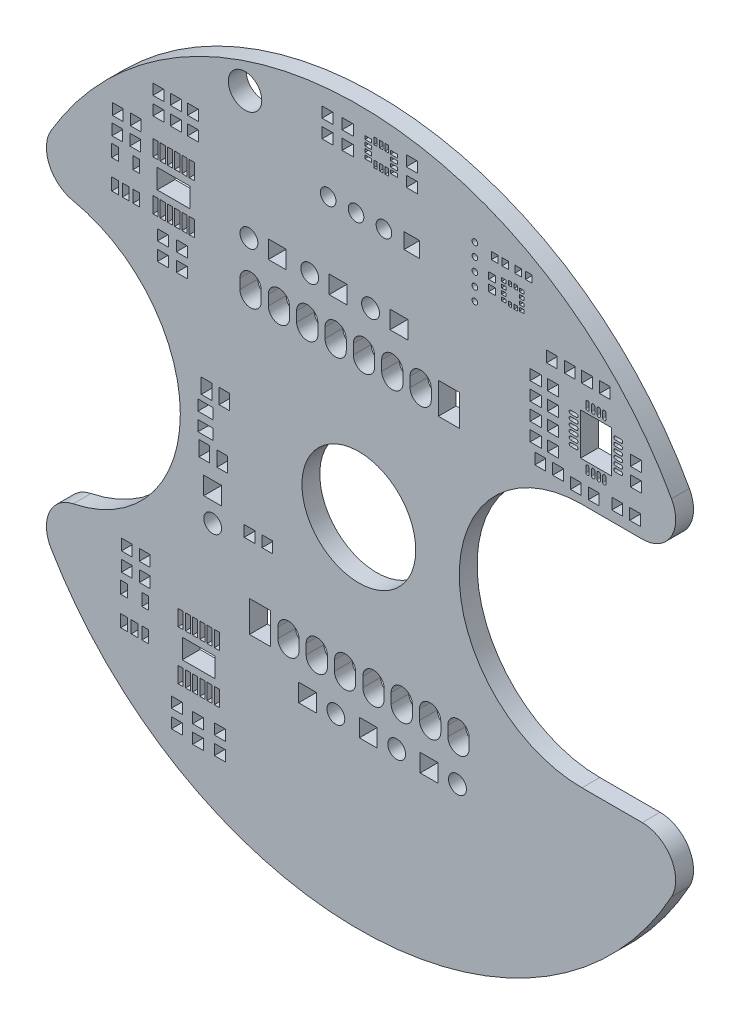
SolidWorks part; units mm, degrees
ref_plane "Plan de face" through (0, 0, 0) normal (0, 0, 1) x (1, 0, 0)
ref_plane "Plan de dessus" through (0, 0, 0) normal (0, 1, 0) x (1, 0, 0)
ref_plane "Plan de droite" through (0, 0, 0) normal (1, 0, 0) x (0, 0, -1)
sketch "Model" plane through (0, 0, 0) normal (0, 0, 1) x (1, 0, 0)
  line L0 (14.8, 23.5) -> (14.8, 23.2)
  line L1 (14.8, 23.2) -> (14.4, 23.2)
  line L2 (14.4, 23.2) -> (14.4, 23.5)
  line L3 (14.4, 23.5) -> (14.8, 23.5)
  line L4 (14.8, 24) -> (14.8, 23.7)
  line L5 (14.8, 23.7) -> (14.4, 23.7)
  line L6 (14.4, 23.7) -> (14.4, 24)
  line L7 (14.4, 24) -> (14.8, 24)
  line L8 (14.8, 24.5) -> (14.8, 24.2)
  line L9 (14.8, 24.2) -> (14.4, 24.2)
  line L10 (14.4, 24.2) -> (14.4, 24.5)
  line L11 (14.4, 24.5) -> (14.8, 24.5)
  line L12 (14.8, 25) -> (14.8, 24.7)
  line L13 (14.8, 24.7) -> (14.4, 24.7)
  line L14 (14.4, 24.7) -> (14.4, 25)
  line L15 (14.4, 25) -> (14.8, 25)
  line L16 (13.9, 25.1) -> (14.2, 25.1)
  line L17 (14.2, 25.1) -> (14.2, 24.7)
  line L18 (14.2, 24.7) -> (13.9, 24.7)
  line L19 (13.9, 24.7) -> (13.9, 25.1)
  line L20 (13.4, 25.1) -> (13.7, 25.1)
  line L21 (13.7, 25.1) -> (13.7, 24.7)
  line L22 (13.7, 24.7) -> (13.4, 24.7)
  line L23 (13.4, 24.7) -> (13.4, 25.1)
  line L24 (13.2, 25) -> (13.2, 24.7)
  line L25 (13.2, 24.7) -> (12.8, 24.7)
  line L26 (12.8, 24.7) -> (12.8, 25)
  line L27 (12.8, 25) -> (13.2, 25)
  line L28 (13.2, 24.5) -> (13.2, 24.2)
  line L29 (13.2, 24.2) -> (12.8, 24.2)
  line L30 (12.8, 24.2) -> (12.8, 24.5)
  line L31 (12.8, 24.5) -> (13.2, 24.5)
  line L32 (13.2, 24) -> (13.2, 23.7)
  line L33 (13.2, 23.7) -> (12.8, 23.7)
  line L34 (12.8, 23.7) -> (12.8, 24)
  line L35 (12.8, 24) -> (13.2, 24)
  line L36 (13.2, 23.5) -> (13.2, 23.2)
  line L37 (13.2, 23.2) -> (12.8, 23.2)
  line L38 (12.8, 23.2) -> (12.8, 23.5)
  line L39 (12.8, 23.5) -> (13.2, 23.5)
  line L40 (13.4, 23.5) -> (13.7, 23.5)
  line L41 (13.7, 23.5) -> (13.7, 23.1)
  line L42 (13.7, 23.1) -> (13.4, 23.1)
  line L43 (13.4, 23.1) -> (13.4, 23.5)
  line L44 (13.9, 23.5) -> (14.2, 23.5)
  line L45 (14.2, 23.5) -> (14.2, 23.1)
  line L46 (14.2, 23.1) -> (13.9, 23.1)
  line L47 (13.9, 23.1) -> (13.9, 23.5)
  line L48 (14.565, 25.93) -> (13.975, 25.93)
  line L49 (13.975, 25.93) -> (13.975, 26.57)
  line L50 (13.975, 26.57) -> (14.565, 26.57)
  line L51 (14.565, 26.57) -> (14.565, 25.93)
  line L52 (15.525, 25.93) -> (14.935, 25.93)
  line L53 (14.935, 25.93) -> (14.935, 26.57)
  line L54 (14.935, 26.57) -> (15.525, 26.57)
  line L55 (15.525, 26.57) -> (15.525, 25.93)
  line L56 (12.835, 26.57) -> (13.425, 26.57)
  line L57 (13.425, 26.57) -> (13.425, 25.93)
  line L58 (13.425, 25.93) -> (12.835, 25.93)
  line L59 (12.835, 25.93) -> (12.835, 26.57)
  line L60 (11.875, 26.57) -> (12.465, 26.57)
  line L61 (12.465, 26.57) -> (12.465, 25.93)
  line L62 (12.465, 25.93) -> (11.875, 25.93)
  line L63 (11.875, 25.93) -> (11.875, 26.57)
  line L64 (11.63, 24.285) -> (11.63, 24.875)
  line L65 (11.63, 24.875) -> (12.27, 24.875)
  line L66 (12.27, 24.875) -> (12.27, 24.285)
  line L67 (12.27, 24.285) -> (11.63, 24.285)
  line L68 (11.63, 23.325) -> (11.63, 23.915)
  line L69 (11.63, 23.915) -> (12.27, 23.915)
  line L70 (12.27, 23.915) -> (12.27, 23.325)
  line L71 (12.27, 23.325) -> (11.63, 23.325)
  line L72 (-12.725, -1.125) -> (-11.775, -1.125)
  line L73 (-11.775, -1.125) -> (-11.775, -2.475)
  line L74 (-11.775, -2.475) -> (-12.725, -2.475)
  line L75 (-12.725, -2.475) -> (-12.725, -1.125)
  line L76 (-14.325, -1.125) -> (-13.375, -1.125)
  line L77 (-13.375, -1.125) -> (-13.375, -2.475)
  line L78 (-13.375, -2.475) -> (-14.325, -2.475)
  line L79 (-14.325, -2.475) -> (-14.325, -1.125)
  line L80 (-12.525, 3.825) -> (-11.575, 3.825)
  line L81 (-11.575, 3.825) -> (-11.575, 2.475)
  line L82 (-11.575, 2.475) -> (-12.525, 2.475)
  line L83 (-12.525, 2.475) -> (-12.525, 3.825)
  line L84 (-14.125, 3.825) -> (-13.175, 3.825)
  line L85 (-13.175, 3.825) -> (-13.175, 2.475)
  line L86 (-13.175, 2.475) -> (-14.125, 2.475)
  line L87 (-14.125, 2.475) -> (-14.125, 3.825)
  line L88 (-13.075, 0.375) -> (-13.075, -0.575)
  line L89 (-13.075, -0.575) -> (-14.425, -0.575)
  line L90 (-14.425, -0.575) -> (-14.425, 0.375)
  line L91 (-14.425, 0.375) -> (-13.075, 0.375)
  line L92 (-13.075, 1.975) -> (-13.075, 1.025)
  line L93 (-13.075, 1.025) -> (-14.425, 1.025)
  line L94 (-14.425, 1.025) -> (-14.425, 1.975)
  line L95 (-14.425, 1.975) -> (-13.075, 1.975)
  line L96 (-21.55, 14.25) -> (-22.15, 14.25)
  line L97 (-22.15, 14.25) -> (-22.15, 15.35)
  line L98 (-22.15, 15.35) -> (-21.55, 15.35)
  line L99 (-21.55, 15.35) -> (-21.55, 14.25)
  line L100 (-20.6, 14.25) -> (-21.2, 14.25)
  line L101 (-21.2, 14.25) -> (-21.2, 15.35)
  line L102 (-21.2, 15.35) -> (-20.6, 15.35)
  line L103 (-20.6, 15.35) -> (-20.6, 14.25)
  line L104 (-19.65, 14.25) -> (-20.25, 14.25)
  line L105 (-20.25, 14.25) -> (-20.25, 15.35)
  line L106 (-20.25, 15.35) -> (-19.65, 15.35)
  line L107 (-19.65, 15.35) -> (-19.65, 14.25)
  line L108 (-19.65, 16.85) -> (-20.25, 16.85)
  line L109 (-20.25, 16.85) -> (-20.25, 17.95)
  line L110 (-20.25, 17.95) -> (-19.65, 17.95)
  line L111 (-19.65, 17.95) -> (-19.65, 16.85)
  line L112 (-21.55, 16.85) -> (-22.15, 16.85)
  line L113 (-22.15, 16.85) -> (-22.15, 17.95)
  line L114 (-22.15, 17.95) -> (-21.55, 17.95)
  line L115 (-21.55, 17.95) -> (-21.55, 16.85)
  line L116 (-20.75, -19.25) -> (-21.35, -19.25)
  line L117 (-21.35, -19.25) -> (-21.35, -18.15)
  line L118 (-21.35, -18.15) -> (-20.75, -18.15)
  line L119 (-20.75, -18.15) -> (-20.75, -19.25)
  line L120 (-19.8, -19.25) -> (-20.4, -19.25)
  line L121 (-20.4, -19.25) -> (-20.4, -18.15)
  line L122 (-20.4, -18.15) -> (-19.8, -18.15)
  line L123 (-19.8, -18.15) -> (-19.8, -19.25)
  line L124 (-18.85, -19.25) -> (-19.45, -19.25)
  line L125 (-19.45, -19.25) -> (-19.45, -18.15)
  line L126 (-19.45, -18.15) -> (-18.85, -18.15)
  line L127 (-18.85, -18.15) -> (-18.85, -19.25)
  line L128 (-18.85, -16.65) -> (-19.45, -16.65)
  line L129 (-19.45, -16.65) -> (-19.45, -15.55)
  line L130 (-19.45, -15.55) -> (-18.85, -15.55)
  line L131 (-18.85, -15.55) -> (-18.85, -16.65)
  line L132 (-20.75, -16.65) -> (-21.35, -16.65)
  line L133 (-21.35, -16.65) -> (-21.35, -15.55)
  line L134 (-21.35, -15.55) -> (-20.75, -15.55)
  line L135 (-20.75, -15.55) -> (-20.75, -16.65)
  line L136 (-18, 15.7505) -> (-18, 14.3255)
  line L137 (-18, 14.3255) -> (-18.45, 14.3255)
  line L138 (-18.45, 14.3255) -> (-18.45, 15.7505)
  line L139 (-18.45, 15.7505) -> (-18, 15.7505)
  line L140 (-17.35, 15.7505) -> (-17.35, 14.3255)
  line L141 (-17.35, 14.3255) -> (-17.8, 14.3255)
  line L142 (-17.8, 14.3255) -> (-17.8, 15.7505)
  line L143 (-17.8, 15.7505) -> (-17.35, 15.7505)
  line L144 (-16.7, 15.7505) -> (-16.7, 14.3255)
  line L145 (-16.7, 14.3255) -> (-17.15, 14.3255)
  line L146 (-17.15, 14.3255) -> (-17.15, 15.7505)
  line L147 (-17.15, 15.7505) -> (-16.7, 15.7505)
  line L148 (-16.05, 15.7505) -> (-16.05, 14.3255)
  line L149 (-16.05, 14.3255) -> (-16.5, 14.3255)
  line L150 (-16.5, 14.3255) -> (-16.5, 15.7505)
  line L151 (-16.5, 15.7505) -> (-16.05, 15.7505)
  line L152 (-15.4, 15.7505) -> (-15.4, 14.3255)
  line L153 (-15.4, 14.3255) -> (-15.85, 14.3255)
  line L154 (-15.85, 14.3255) -> (-15.85, 15.7505)
  line L155 (-15.85, 15.7505) -> (-15.4, 15.7505)
  line L156 (-14.75, 15.7505) -> (-14.75, 14.3255)
  line L157 (-14.75, 14.3255) -> (-15.2, 14.3255)
  line L158 (-15.2, 14.3255) -> (-15.2, 15.7505)
  line L159 (-15.2, 15.7505) -> (-14.75, 15.7505)
  line L160 (-14.75, 20.1745) -> (-14.75, 18.7495)
  line L161 (-14.75, 18.7495) -> (-15.2, 18.7495)
  line L162 (-15.2, 18.7495) -> (-15.2, 20.1745)
  line L163 (-15.2, 20.1745) -> (-14.75, 20.1745)
  line L164 (-15.4, 20.1745) -> (-15.4, 18.7495)
  line L165 (-15.4, 18.7495) -> (-15.85, 18.7495)
  line L166 (-15.85, 18.7495) -> (-15.85, 20.1745)
  line L167 (-15.85, 20.1745) -> (-15.4, 20.1745)
  line L168 (-16.05, 20.1745) -> (-16.05, 18.7495)
  line L169 (-16.05, 18.7495) -> (-16.5, 18.7495)
  line L170 (-16.5, 18.7495) -> (-16.5, 20.1745)
  line L171 (-16.5, 20.1745) -> (-16.05, 20.1745)
  line L172 (-16.7, 20.1745) -> (-16.7, 18.7495)
  line L173 (-16.7, 18.7495) -> (-17.15, 18.7495)
  line L174 (-17.15, 18.7495) -> (-17.15, 20.1745)
  line L175 (-17.15, 20.1745) -> (-16.7, 20.1745)
  line L176 (-17.35, 20.1745) -> (-17.35, 18.7495)
  line L177 (-17.35, 18.7495) -> (-17.8, 18.7495)
  line L178 (-17.8, 18.7495) -> (-17.8, 20.1745)
  line L179 (-17.8, 20.1745) -> (-17.35, 20.1745)
  line L180 (-18, 20.1745) -> (-18, 18.7495)
  line L181 (-18, 18.7495) -> (-18.45, 18.7495)
  line L182 (-18.45, 18.7495) -> (-18.45, 20.1745)
  line L183 (-18.45, 20.1745) -> (-18, 20.1745)
  line L184 (-18.0735, 18.1265) -> (-15.1265, 18.1265)
  line L185 (-15.1265, 18.1265) -> (-15.1265, 16.3735)
  line L186 (-15.1265, 16.3735) -> (-18.0735, 16.3735)
  line L187 (-18.0735, 16.3735) -> (-18.0735, 18.1265)
  line L188 (-12.95, -16.6005) -> (-12.95, -15.1755)
  line L189 (-12.95, -15.1755) -> (-12.5, -15.1755)
  line L190 (-12.5, -15.1755) -> (-12.5, -16.6005)
  line L191 (-12.5, -16.6005) -> (-12.95, -16.6005)
  line L192 (-13.6, -16.6005) -> (-13.6, -15.1755)
  line L193 (-13.6, -15.1755) -> (-13.15, -15.1755)
  line L194 (-13.15, -15.1755) -> (-13.15, -16.6005)
  line L195 (-13.15, -16.6005) -> (-13.6, -16.6005)
  line L196 (-14.25, -16.6005) -> (-14.25, -15.1755)
  line L197 (-14.25, -15.1755) -> (-13.8, -15.1755)
  line L198 (-13.8, -15.1755) -> (-13.8, -16.6005)
  line L199 (-13.8, -16.6005) -> (-14.25, -16.6005)
  line L200 (-14.9, -16.6005) -> (-14.9, -15.1755)
  line L201 (-14.9, -15.1755) -> (-14.45, -15.1755)
  line L202 (-14.45, -15.1755) -> (-14.45, -16.6005)
  line L203 (-14.45, -16.6005) -> (-14.9, -16.6005)
  line L204 (-15.55, -16.6005) -> (-15.55, -15.1755)
  line L205 (-15.55, -15.1755) -> (-15.1, -15.1755)
  line L206 (-15.1, -15.1755) -> (-15.1, -16.6005)
  line L207 (-15.1, -16.6005) -> (-15.55, -16.6005)
  line L208 (-16.2, -16.6005) -> (-16.2, -15.1755)
  line L209 (-16.2, -15.1755) -> (-15.75, -15.1755)
  line L210 (-15.75, -15.1755) -> (-15.75, -16.6005)
  line L211 (-15.75, -16.6005) -> (-16.2, -16.6005)
  line L212 (-16.2, -21.0245) -> (-16.2, -19.5995)
  line L213 (-16.2, -19.5995) -> (-15.75, -19.5995)
  line L214 (-15.75, -19.5995) -> (-15.75, -21.0245)
  line L215 (-15.75, -21.0245) -> (-16.2, -21.0245)
  line L216 (-15.55, -21.0245) -> (-15.55, -19.5995)
  line L217 (-15.55, -19.5995) -> (-15.1, -19.5995)
  line L218 (-15.1, -19.5995) -> (-15.1, -21.0245)
  line L219 (-15.1, -21.0245) -> (-15.55, -21.0245)
  line L220 (-14.9, -21.0245) -> (-14.9, -19.5995)
  line L221 (-14.9, -19.5995) -> (-14.45, -19.5995)
  line L222 (-14.45, -19.5995) -> (-14.45, -21.0245)
  line L223 (-14.45, -21.0245) -> (-14.9, -21.0245)
  line L224 (-14.25, -21.0245) -> (-14.25, -19.5995)
  line L225 (-14.25, -19.5995) -> (-13.8, -19.5995)
  line L226 (-13.8, -19.5995) -> (-13.8, -21.0245)
  line L227 (-13.8, -21.0245) -> (-14.25, -21.0245)
  line L228 (-13.6, -21.0245) -> (-13.6, -19.5995)
  line L229 (-13.6, -19.5995) -> (-13.15, -19.5995)
  line L230 (-13.15, -19.5995) -> (-13.15, -21.0245)
  line L231 (-13.15, -21.0245) -> (-13.6, -21.0245)
  line L232 (-12.95, -21.0245) -> (-12.95, -19.5995)
  line L233 (-12.95, -19.5995) -> (-12.5, -19.5995)
  line L234 (-12.5, -19.5995) -> (-12.5, -21.0245)
  line L235 (-12.5, -21.0245) -> (-12.95, -21.0245)
  line L236 (-12.8765, -18.9765) -> (-15.8235, -18.9765)
  line L237 (-15.8235, -18.9765) -> (-15.8235, -17.2235)
  line L238 (-15.8235, -17.2235) -> (-12.8765, -17.2235)
  line L239 (-12.8765, -17.2235) -> (-12.8765, -18.9765)
  line L240 (9.0325, 14.197) -> (9.0325, 11.403)
  line L241 (9.0325, 11.403) -> (7.1275, 11.403)
  line L242 (7.1275, 11.403) -> (7.1275, 14.197)
  line L243 (7.1275, 14.197) -> (9.0325, 14.197)
  line L244 (4.5875, 12.3555) -> (4.5875, 13.2445)
  line L245 (6.4925, 13.2445) -> (6.4925, 12.3555)
  line L246 (2.0475, 12.3555) -> (2.0475, 13.2445)
  line L247 (3.9525, 13.2445) -> (3.9525, 12.3555)
  line L248 (-0.4925, 12.3555) -> (-0.4925, 13.2445)
  line L249 (1.4125, 13.2445) -> (1.4125, 12.3555)
  line L250 (-3.0325, 12.3555) -> (-3.0325, 13.2445)
  line L251 (-1.1275, 13.2445) -> (-1.1275, 12.3555)
  line L252 (-5.5725, 12.3555) -> (-5.5725, 13.2445)
  line L253 (-3.6675, 13.2445) -> (-3.6675, 12.3555)
  line L254 (-8.1125, 12.3555) -> (-8.1125, 13.2445)
  line L255 (-6.2075, 13.2445) -> (-6.2075, 12.3555)
  line L256 (-10.6525, 12.3555) -> (-10.6525, 13.2445)
  line L257 (-8.7475, 13.2445) -> (-8.7475, 12.3555)
  line L258 (-9.8025, -13.997) -> (-9.8025, -11.203)
  line L259 (-9.8025, -11.203) -> (-7.8975, -11.203)
  line L260 (-7.8975, -11.203) -> (-7.8975, -13.997)
  line L261 (-7.8975, -13.997) -> (-9.8025, -13.997)
  line L262 (-5.3575, -12.1555) -> (-5.3575, -13.0445)
  line L263 (-7.2625, -13.0445) -> (-7.2625, -12.1555)
  line L264 (-2.8175, -12.1555) -> (-2.8175, -13.0445)
  line L265 (-4.7225, -13.0445) -> (-4.7225, -12.1555)
  line L266 (-0.2775, -12.1555) -> (-0.2775, -13.0445)
  line L267 (-2.1825, -13.0445) -> (-2.1825, -12.1555)
  line L268 (2.2625, -12.1555) -> (2.2625, -13.0445)
  line L269 (0.3575, -13.0445) -> (0.3575, -12.1555)
  line L270 (4.8025, -12.1555) -> (4.8025, -13.0445)
  line L271 (2.8975, -13.0445) -> (2.8975, -12.1555)
  line L272 (7.3425, -12.1555) -> (7.3425, -13.0445)
  line L273 (5.4375, -13.0445) -> (5.4375, -12.1555)
  line L274 (9.8825, -12.1555) -> (9.8825, -13.0445)
  line L275 (7.9775, -13.0445) -> (7.9775, -12.1555)
  line L276 (3.45, 28.4) -> (3.45, 28.1)
  line L277 (3.45, 28.1) -> (2.85, 28.1)
  line L278 (2.85, 28.1) -> (2.85, 28.4)
  line L279 (2.85, 28.4) -> (3.45, 28.4)
  line L280 (3.45, 28.9) -> (3.45, 28.6)
  line L281 (3.45, 28.6) -> (2.85, 28.6)
  line L282 (2.85, 28.6) -> (2.85, 28.9)
  line L283 (2.85, 28.9) -> (3.45, 28.9)
  line L284 (3.45, 29.4) -> (3.45, 29.1)
  line L285 (3.45, 29.1) -> (2.85, 29.1)
  line L286 (2.85, 29.1) -> (2.85, 29.4)
  line L287 (2.85, 29.4) -> (3.45, 29.4)
  line L288 (3.45, 29.9) -> (3.45, 29.6)
  line L289 (3.45, 29.6) -> (2.85, 29.6)
  line L290 (2.85, 29.6) -> (2.85, 29.9)
  line L291 (2.85, 29.9) -> (3.45, 29.9)
  line L292 (2.35, 30.2) -> (2.65, 30.2)
  line L293 (2.65, 30.2) -> (2.65, 29.6)
  line L294 (2.65, 29.6) -> (2.35, 29.6)
  line L295 (2.35, 29.6) -> (2.35, 30.2)
  line L296 (1.85, 30.2) -> (2.15, 30.2)
  line L297 (2.15, 30.2) -> (2.15, 29.6)
  line L298 (2.15, 29.6) -> (1.85, 29.6)
  line L299 (1.85, 29.6) -> (1.85, 30.2)
  line L300 (1.35, 30.2) -> (1.65, 30.2)
  line L301 (1.65, 30.2) -> (1.65, 29.6)
  line L302 (1.65, 29.6) -> (1.35, 29.6)
  line L303 (1.35, 29.6) -> (1.35, 30.2)
  line L304 (1.15, 29.9) -> (1.15, 29.6)
  line L305 (1.15, 29.6) -> (0.55, 29.6)
  line L306 (0.55, 29.6) -> (0.55, 29.9)
  line L307 (0.55, 29.9) -> (1.15, 29.9)
  line L308 (1.15, 29.4) -> (1.15, 29.1)
  line L309 (1.15, 29.1) -> (0.55, 29.1)
  line L310 (0.55, 29.1) -> (0.55, 29.4)
  line L311 (0.55, 29.4) -> (1.15, 29.4)
  line L312 (1.15, 28.9) -> (1.15, 28.6)
  line L313 (1.15, 28.6) -> (0.55, 28.6)
  line L314 (0.55, 28.6) -> (0.55, 28.9)
  line L315 (0.55, 28.9) -> (1.15, 28.9)
  line L316 (1.15, 28.4) -> (1.15, 28.1)
  line L317 (1.15, 28.1) -> (0.55, 28.1)
  line L318 (0.55, 28.1) -> (0.55, 28.4)
  line L319 (0.55, 28.4) -> (1.15, 28.4)
  line L320 (1.35, 28.4) -> (1.65, 28.4)
  line L321 (1.65, 28.4) -> (1.65, 27.8)
  line L322 (1.65, 27.8) -> (1.35, 27.8)
  line L323 (1.35, 27.8) -> (1.35, 28.4)
  line L324 (1.85, 28.4) -> (2.15, 28.4)
  line L325 (2.15, 28.4) -> (2.15, 27.8)
  line L326 (2.15, 27.8) -> (1.85, 27.8)
  line L327 (1.85, 27.8) -> (1.85, 28.4)
  line L328 (2.35, 28.4) -> (2.65, 28.4)
  line L329 (2.65, 28.4) -> (2.65, 27.8)
  line L330 (2.65, 27.8) -> (2.35, 27.8)
  line L331 (2.35, 27.8) -> (2.35, 28.4)
  line L332 (23, 15.3) -> (23.5, 15.3)
  line L333 (23.5, 15) -> (23, 15)
  line L334 (23, 15.8) -> (23.5, 15.8)
  line L335 (23.5, 15.5) -> (23, 15.5)
  line L336 (23, 16.3) -> (23.5, 16.3)
  line L337 (23.5, 16) -> (23, 16)
  line L338 (23, 16.8) -> (23.5, 16.8)
  line L339 (23.5, 16.5) -> (23, 16.5)
  line L340 (23, 17.3) -> (23.5, 17.3)
  line L341 (23.5, 17) -> (23, 17)
  line L342 (23, 17.8) -> (23.5, 17.8)
  line L343 (23.5, 17.5) -> (23, 17.5)
  line L344 (21.85, 18.65) -> (21.85, 19.15)
  line L345 (22.15, 19.15) -> (22.15, 18.65)
  line L346 (21.35, 18.65) -> (21.35, 19.15)
  line L347 (21.65, 19.15) -> (21.65, 18.65)
  line L348 (20.85, 18.65) -> (20.85, 19.15)
  line L349 (21.15, 19.15) -> (21.15, 18.65)
  line L350 (20.35, 18.65) -> (20.35, 19.15)
  line L351 (20.65, 19.15) -> (20.65, 18.65)
  line L352 (19, 17.8) -> (19.5, 17.8)
  line L353 (19.5, 17.5) -> (19, 17.5)
  line L354 (19, 17.3) -> (19.5, 17.3)
  line L355 (19.5, 17) -> (19, 17)
  line L356 (19, 16.8) -> (19.5, 16.8)
  line L357 (19.5, 16.5) -> (19, 16.5)
  line L358 (19, 16.3) -> (19.5, 16.3)
  line L359 (19.5, 16) -> (19, 16)
  line L360 (19, 15.8) -> (19.5, 15.8)
  line L361 (19.5, 15.5) -> (19, 15.5)
  line L362 (19, 15.3) -> (19.5, 15.3)
  line L363 (19.5, 15) -> (19, 15)
  line L364 (20.35, 13.65) -> (20.35, 14.15)
  line L365 (20.65, 14.15) -> (20.65, 13.65)
  line L366 (20.85, 13.65) -> (20.85, 14.15)
  line L367 (21.15, 14.15) -> (21.15, 13.65)
  line L368 (21.35, 13.65) -> (21.35, 14.15)
  line L369 (21.65, 14.15) -> (21.65, 13.65)
  line L370 (21.85, 13.65) -> (21.85, 14.15)
  line L371 (22.15, 14.15) -> (22.15, 13.65)
  line L372 (22.625, 18.275) -> (22.625, 14.525)
  line L373 (22.625, 14.525) -> (19.875, 14.525)
  line L374 (19.875, 14.525) -> (19.875, 18.275)
  line L375 (19.875, 18.275) -> (22.625, 18.275)
  line L376 (-9.325, -6.7) -> (-10.275, -6.7)
  line L377 (-10.275, -6.7) -> (-10.275, -5.7)
  line L378 (-10.275, -5.7) -> (-9.325, -5.7)
  line L379 (-9.325, -5.7) -> (-9.325, -6.7)
  line L380 (-7.725, -6.7) -> (-8.675, -6.7)
  line L381 (-8.675, -6.7) -> (-8.675, -5.7)
  line L382 (-8.675, -5.7) -> (-7.725, -5.7)
  line L383 (-7.725, -5.7) -> (-7.725, -6.7)
  line L384 (-21.125, 20.15) -> (-22.075, 20.15)
  line L385 (-22.075, 20.15) -> (-22.075, 21.15)
  line L386 (-22.075, 21.15) -> (-21.125, 21.15)
  line L387 (-21.125, 21.15) -> (-21.125, 20.15)
  line L388 (-19.525, 20.15) -> (-20.475, 20.15)
  line L389 (-20.475, 20.15) -> (-20.475, 21.15)
  line L390 (-20.475, 21.15) -> (-19.525, 21.15)
  line L391 (-19.525, 21.15) -> (-19.525, 20.15)
  line L392 (-20.325, -13.25) -> (-21.275, -13.25)
  line L393 (-21.275, -13.25) -> (-21.275, -12.25)
  line L394 (-21.275, -12.25) -> (-20.325, -12.25)
  line L395 (-20.325, -12.25) -> (-20.325, -13.25)
  line L396 (-18.725, -13.25) -> (-19.675, -13.25)
  line L397 (-19.675, -13.25) -> (-19.675, -12.25)
  line L398 (-19.675, -12.25) -> (-18.725, -12.25)
  line L399 (-18.725, -12.25) -> (-18.725, -13.25)
  line L400 (-21.175, 18.55) -> (-22.125, 18.55)
  line L401 (-22.125, 18.55) -> (-22.125, 19.55)
  line L402 (-22.125, 19.55) -> (-21.175, 19.55)
  line L403 (-21.175, 19.55) -> (-21.175, 18.55)
  line L404 (-19.575, 18.55) -> (-20.525, 18.55)
  line L405 (-20.525, 18.55) -> (-20.525, 19.55)
  line L406 (-20.525, 19.55) -> (-19.575, 19.55)
  line L407 (-19.575, 19.55) -> (-19.575, 18.55)
  line L408 (-20.325, -14.9) -> (-21.275, -14.9)
  line L409 (-21.275, -14.9) -> (-21.275, -13.9)
  line L410 (-21.275, -13.9) -> (-20.325, -13.9)
  line L411 (-20.325, -13.9) -> (-20.325, -14.9)
  line L412 (-18.725, -14.9) -> (-19.675, -14.9)
  line L413 (-19.675, -14.9) -> (-19.675, -13.9)
  line L414 (-19.675, -13.9) -> (-18.725, -13.9)
  line L415 (-18.725, -13.9) -> (-18.725, -14.9)
  line L416 (-18.45, 23.525) -> (-18.45, 24.475)
  line L417 (-18.45, 24.475) -> (-17.45, 24.475)
  line L418 (-17.45, 24.475) -> (-17.45, 23.525)
  line L419 (-17.45, 23.525) -> (-18.45, 23.525)
  line L420 (-18.45, 21.925) -> (-18.45, 22.875)
  line L421 (-18.45, 22.875) -> (-17.45, 22.875)
  line L422 (-17.45, 22.875) -> (-17.45, 21.925)
  line L423 (-17.45, 21.925) -> (-18.45, 21.925)
  line L424 (20.925, 20.4) -> (19.975, 20.4)
  line L425 (19.975, 20.4) -> (19.975, 21.4)
  line L426 (19.975, 21.4) -> (20.925, 21.4)
  line L427 (20.925, 21.4) -> (20.925, 20.4)
  line L428 (22.525, 20.4) -> (21.575, 20.4)
  line L429 (21.575, 20.4) -> (21.575, 21.4)
  line L430 (21.575, 21.4) -> (22.525, 21.4)
  line L431 (22.525, 21.4) -> (22.525, 20.4)
  line L432 (-15.9, 22.875) -> (-15.9, 21.925)
  line L433 (-15.9, 21.925) -> (-16.9, 21.925)
  line L434 (-16.9, 21.925) -> (-16.9, 22.875)
  line L435 (-16.9, 22.875) -> (-15.9, 22.875)
  line L436 (-15.9, 24.475) -> (-15.9, 23.525)
  line L437 (-15.9, 23.525) -> (-16.9, 23.525)
  line L438 (-16.9, 23.525) -> (-16.9, 24.475)
  line L439 (-16.9, 24.475) -> (-15.9, 24.475)
  line L440 (-14.9, -23.475) -> (-14.9, -22.525)
  line L441 (-14.9, -22.525) -> (-13.9, -22.525)
  line L442 (-13.9, -22.525) -> (-13.9, -23.475)
  line L443 (-13.9, -23.475) -> (-14.9, -23.475)
  line L444 (-14.9, -25.075) -> (-14.9, -24.125)
  line L445 (-14.9, -24.125) -> (-13.9, -24.125)
  line L446 (-13.9, -24.125) -> (-13.9, -25.075)
  line L447 (-13.9, -25.075) -> (-14.9, -25.075)
  line L448 (-18.05, 12.425) -> (-18.05, 13.375)
  line L449 (-18.05, 13.375) -> (-17.05, 13.375)
  line L450 (-17.05, 13.375) -> (-17.05, 12.425)
  line L451 (-17.05, 12.425) -> (-18.05, 12.425)
  line L452 (-18.05, 10.825) -> (-18.05, 11.775)
  line L453 (-18.05, 11.775) -> (-17.05, 11.775)
  line L454 (-17.05, 11.775) -> (-17.05, 10.825)
  line L455 (-17.05, 10.825) -> (-18.05, 10.825)
  line L456 (-15.35, 11.775) -> (-15.35, 10.825)
  line L457 (-15.35, 10.825) -> (-16.35, 10.825)
  line L458 (-16.35, 10.825) -> (-16.35, 11.775)
  line L459 (-16.35, 11.775) -> (-15.35, 11.775)
  line L460 (-15.35, 13.375) -> (-15.35, 12.425)
  line L461 (-15.35, 12.425) -> (-16.35, 12.425)
  line L462 (-16.35, 12.425) -> (-16.35, 13.375)
  line L463 (-16.35, 13.375) -> (-15.35, 13.375)
  line L464 (-15.35, 23.525) -> (-15.35, 24.475)
  line L465 (-15.35, 24.475) -> (-14.35, 24.475)
  line L466 (-14.35, 24.475) -> (-14.35, 23.525)
  line L467 (-14.35, 23.525) -> (-15.35, 23.525)
  line L468 (-15.35, 21.925) -> (-15.35, 22.875)
  line L469 (-15.35, 22.875) -> (-14.35, 22.875)
  line L470 (-14.35, 22.875) -> (-14.35, 21.925)
  line L471 (-14.35, 21.925) -> (-15.35, 21.925)
  line L472 (4.25, 29.325) -> (4.25, 30.275)
  line L473 (4.25, 30.275) -> (5.25, 30.275)
  line L474 (5.25, 30.275) -> (5.25, 29.325)
  line L475 (5.25, 29.325) -> (4.25, 29.325)
  line L476 (4.25, 27.725) -> (4.25, 28.675)
  line L477 (4.25, 28.675) -> (5.25, 28.675)
  line L478 (5.25, 28.675) -> (5.25, 27.725)
  line L479 (5.25, 27.725) -> (4.25, 27.725)
  line L480 (-2.3, 28.675) -> (-2.3, 27.725)
  line L481 (-2.3, 27.725) -> (-3.3, 27.725)
  line L482 (-3.3, 27.725) -> (-3.3, 28.675)
  line L483 (-3.3, 28.675) -> (-2.3, 28.675)
  line L484 (-2.3, 30.275) -> (-2.3, 29.325)
  line L485 (-2.3, 29.325) -> (-3.3, 29.325)
  line L486 (-3.3, 29.325) -> (-3.3, 30.275)
  line L487 (-3.3, 30.275) -> (-2.3, 30.275)
  line L488 (-0.5, 28.675) -> (-0.5, 27.725)
  line L489 (-0.5, 27.725) -> (-1.5, 27.725)
  line L490 (-1.5, 27.725) -> (-1.5, 28.675)
  line L491 (-1.5, 28.675) -> (-0.5, 28.675)
  line L492 (-0.5, 30.275) -> (-0.5, 29.325)
  line L493 (-0.5, 29.325) -> (-1.5, 29.325)
  line L494 (-1.5, 29.325) -> (-1.5, 30.275)
  line L495 (-1.5, 30.275) -> (-0.5, 30.275)
  line L496 (16.725, 11.95) -> (15.775, 11.95)
  line L497 (15.775, 11.95) -> (15.775, 12.95)
  line L498 (15.775, 12.95) -> (16.725, 12.95)
  line L499 (16.725, 12.95) -> (16.725, 11.95)
  line L500 (18.325, 11.95) -> (17.375, 11.95)
  line L501 (17.375, 11.95) -> (17.375, 12.95)
  line L502 (17.375, 12.95) -> (18.325, 12.95)
  line L503 (18.325, 12.95) -> (18.325, 11.95)
  line L504 (19.925, 11.65) -> (18.975, 11.65)
  line L505 (18.975, 11.65) -> (18.975, 12.65)
  line L506 (18.975, 12.65) -> (19.925, 12.65)
  line L507 (19.925, 12.65) -> (19.925, 11.65)
  line L508 (21.525, 11.65) -> (20.575, 11.65)
  line L509 (20.575, 11.65) -> (20.575, 12.65)
  line L510 (20.575, 12.65) -> (21.525, 12.65)
  line L511 (21.525, 12.65) -> (21.525, 11.65)
  line L512 (17.775, 20.4) -> (16.825, 20.4)
  line L513 (16.825, 20.4) -> (16.825, 21.4)
  line L514 (16.825, 21.4) -> (17.775, 21.4)
  line L515 (17.775, 21.4) -> (17.775, 20.4)
  line L516 (19.375, 20.4) -> (18.425, 20.4)
  line L517 (18.425, 20.4) -> (18.425, 21.4)
  line L518 (18.425, 21.4) -> (19.375, 21.4)
  line L519 (19.375, 21.4) -> (19.375, 20.4)
  line L520 (25.35, 15.475) -> (25.35, 14.525)
  line L521 (25.35, 14.525) -> (24.35, 14.525)
  line L522 (24.35, 14.525) -> (24.35, 15.475)
  line L523 (24.35, 15.475) -> (25.35, 15.475)
  line L524 (25.35, 17.075) -> (25.35, 16.125)
  line L525 (25.35, 16.125) -> (24.35, 16.125)
  line L526 (24.35, 16.125) -> (24.35, 17.075)
  line L527 (24.35, 17.075) -> (25.35, 17.075)
  line L528 (24.275, 12.9) -> (25.225, 12.9)
  line L529 (25.225, 12.9) -> (25.225, 11.9)
  line L530 (25.225, 11.9) -> (24.275, 11.9)
  line L531 (24.275, 11.9) -> (24.275, 12.9)
  line L532 (22.675, 12.9) -> (23.625, 12.9)
  line L533 (23.625, 12.9) -> (23.625, 11.9)
  line L534 (23.625, 11.9) -> (22.675, 11.9)
  line L535 (22.675, 11.9) -> (22.675, 12.9)
  line L536 (16.35, 14.475) -> (16.35, 13.525)
  line L537 (16.35, 13.525) -> (15.35, 13.525)
  line L538 (15.35, 13.525) -> (15.35, 14.475)
  line L539 (15.35, 14.475) -> (16.35, 14.475)
  line L540 (16.35, 16.075) -> (16.35, 15.125)
  line L541 (16.35, 15.125) -> (15.35, 15.125)
  line L542 (15.35, 15.125) -> (15.35, 16.075)
  line L543 (15.35, 16.075) -> (16.35, 16.075)
  line L544 (17.9, 14.475) -> (17.9, 13.525)
  line L545 (17.9, 13.525) -> (16.9, 13.525)
  line L546 (16.9, 13.525) -> (16.9, 14.475)
  line L547 (16.9, 14.475) -> (17.9, 14.475)
  line L548 (17.9, 16.075) -> (17.9, 15.125)
  line L549 (17.9, 15.125) -> (16.9, 15.125)
  line L550 (16.9, 15.125) -> (16.9, 16.075)
  line L551 (16.9, 16.075) -> (17.9, 16.075)
  line L552 (16.35, 17.625) -> (16.35, 16.675)
  line L553 (16.35, 16.675) -> (15.35, 16.675)
  line L554 (15.35, 16.675) -> (15.35, 17.625)
  line L555 (15.35, 17.625) -> (16.35, 17.625)
  line L556 (16.35, 19.225) -> (16.35, 18.275)
  line L557 (16.35, 18.275) -> (15.35, 18.275)
  line L558 (15.35, 18.275) -> (15.35, 19.225)
  line L559 (15.35, 19.225) -> (16.35, 19.225)
  line L560 (17.9, 17.625) -> (17.9, 16.675)
  line L561 (17.9, 16.675) -> (16.9, 16.675)
  line L562 (16.9, 16.675) -> (16.9, 17.625)
  line L563 (16.9, 17.625) -> (17.9, 17.625)
  line L564 (17.9, 19.225) -> (17.9, 18.275)
  line L565 (17.9, 18.275) -> (16.9, 18.275)
  line L566 (16.9, 18.275) -> (16.9, 19.225)
  line L567 (16.9, 19.225) -> (17.9, 19.225)
  line L568 (-16.8, -23.225) -> (-16.8, -22.275)
  line L569 (-16.8, -22.275) -> (-15.8, -22.275)
  line L570 (-15.8, -22.275) -> (-15.8, -23.225)
  line L571 (-15.8, -23.225) -> (-16.8, -23.225)
  line L572 (-16.8, -24.825) -> (-16.8, -23.875)
  line L573 (-16.8, -23.875) -> (-15.8, -23.875)
  line L574 (-15.8, -23.875) -> (-15.8, -24.825)
  line L575 (-15.8, -24.825) -> (-16.8, -24.825)
  line L576 (-11.95, -24.025) -> (-11.95, -24.975)
  line L577 (-11.95, -24.975) -> (-12.95, -24.975)
  line L578 (-12.95, -24.975) -> (-12.95, -24.025)
  line L579 (-12.95, -24.025) -> (-11.95, -24.025)
  line L580 (-11.95, -22.425) -> (-11.95, -23.375)
  line L581 (-11.95, -23.375) -> (-12.95, -23.375)
  line L582 (-12.95, -23.375) -> (-12.95, -22.425)
  line L583 (-12.95, -22.425) -> (-11.95, -22.425)
  line L584 (5.45, 24.2) -> (5.45, 22.8)
  line L585 (5.45, 22.8) -> (4.05, 22.8)
  line L586 (4.05, 22.8) -> (4.05, 24.2)
  line L587 (4.05, 24.2) -> (5.45, 24.2)
  line L588 (-6.51, 17.55) -> (-6.51, 15.95)
  line L589 (-6.51, 15.95) -> (-8.11, 15.95)
  line L590 (-8.11, 15.95) -> (-8.11, 17.55)
  line L591 (-8.11, 17.55) -> (-6.51, 17.55)
  line L592 (-1.06, 17.55) -> (-1.06, 15.95)
  line L593 (-1.06, 15.95) -> (-2.66, 15.95)
  line L594 (-2.66, 15.95) -> (-2.66, 17.55)
  line L595 (-2.66, 17.55) -> (-1.06, 17.55)
  line L596 (4.39, 17.55) -> (4.39, 15.95)
  line L597 (4.39, 15.95) -> (2.79, 15.95)
  line L598 (2.79, 15.95) -> (2.79, 17.55)
  line L599 (2.79, 17.55) -> (4.39, 17.55)
  line L600 (5.5, -17.1) -> (5.5, -15.5)
  line L601 (5.5, -15.5) -> (7.1, -15.5)
  line L602 (7.1, -15.5) -> (7.1, -17.1)
  line L603 (7.1, -17.1) -> (5.5, -17.1)
  line L604 (0.05, -17.1) -> (0.05, -15.5)
  line L605 (0.05, -15.5) -> (1.65, -15.5)
  line L606 (1.65, -15.5) -> (1.65, -17.1)
  line L607 (1.65, -17.1) -> (0.05, -17.1)
  line L608 (-5.4, -17.1) -> (-5.4, -15.5)
  line L609 (-5.4, -15.5) -> (-3.8, -15.5)
  line L610 (-3.8, -15.5) -> (-3.8, -17.1)
  line L611 (-3.8, -17.1) -> (-5.4, -17.1)
  line L612 (-13.9, -3.68) -> (-12.3, -3.68)
  line L613 (-12.3, -3.68) -> (-12.3, -5.28)
  line L614 (-12.3, -5.28) -> (-13.9, -5.28)
  line L615 (-13.9, -5.28) -> (-13.9, -3.68)
  line L616 (25.3969, -11) -> (20, -11)
  line L617 (20, 11) -> (25.3969, 11)
  circle A0 centre (0, 0) radius 8.5 construction
  circle A1 centre (10.4, 21.95) radius 0.254
  circle A2 centre (10.4, 23.1) radius 0.254
  circle A3 centre (10.4, 24.25) radius 0.254
  circle A4 centre (10.4, 25.4) radius 0.254
  circle A5 centre (10.4, 26.55) radius 0.254
  circle A6 centre (-10.2, 28) radius 1.5
  circle A7 centre (2.25, 23.5) radius 0.7
  circle A8 centre (-0.25, 23.5) radius 0.7
  circle A9 centre (-2.75, 23.5) radius 0.7
  circle A10 centre (-9.85, 16.75) radius 0.8
  circle A11 centre (-4.4, 16.75) radius 0.8
  circle A12 centre (1.05, 16.75) radius 0.8
  circle A13 centre (8.84, -16.3) radius 0.8
  circle A14 centre (3.39, -16.3) radius 0.8
  circle A15 centre (-2.06, -16.3) radius 0.8
  circle A16 centre (-13.1, -7.02) radius 0.8
  arc A17 (6.4925, 13.2445) -> (4.5875, 13.2445) centre (5.54, 13.2445) ccw
  arc A18 (4.5875, 12.3555) -> (6.4925, 12.3555) centre (5.54, 12.3555) ccw
  arc A19 (3.9525, 13.2445) -> (2.0475, 13.2445) centre (3, 13.2445) ccw
  arc A20 (2.0475, 12.3555) -> (3.9525, 12.3555) centre (3, 12.3555) ccw
  arc A21 (1.4125, 13.2445) -> (-0.4925, 13.2445) centre (0.46, 13.2445) ccw
  arc A22 (-0.4925, 12.3555) -> (1.4125, 12.3555) centre (0.46, 12.3555) ccw
  arc A23 (-1.1275, 13.2445) -> (-3.0325, 13.2445) centre (-2.08, 13.2445) ccw
  arc A24 (-3.0325, 12.3555) -> (-1.1275, 12.3555) centre (-2.08, 12.3555) ccw
  arc A25 (-3.6675, 13.2445) -> (-5.5725, 13.2445) centre (-4.62, 13.2445) ccw
  arc A26 (-5.5725, 12.3555) -> (-3.6675, 12.3555) centre (-4.62, 12.3555) ccw
  arc A27 (-6.2075, 13.2445) -> (-8.1125, 13.2445) centre (-7.16, 13.2445) ccw
  arc A28 (-8.1125, 12.3555) -> (-6.2075, 12.3555) centre (-7.16, 12.3555) ccw
  arc A29 (-8.7475, 13.2445) -> (-10.6525, 13.2445) centre (-9.7, 13.2445) ccw
  arc A30 (-10.6525, 12.3555) -> (-8.7475, 12.3555) centre (-9.7, 12.3555) ccw
  arc A31 (-7.2625, -13.0445) -> (-5.3575, -13.0445) centre (-6.31, -13.0445) ccw
  arc A32 (-5.3575, -12.1555) -> (-7.2625, -12.1555) centre (-6.31, -12.1555) ccw
  arc A33 (-4.7225, -13.0445) -> (-2.8175, -13.0445) centre (-3.77, -13.0445) ccw
  arc A34 (-2.8175, -12.1555) -> (-4.7225, -12.1555) centre (-3.77, -12.1555) ccw
  arc A35 (-2.1825, -13.0445) -> (-0.2775, -13.0445) centre (-1.23, -13.0445) ccw
  arc A36 (-0.2775, -12.1555) -> (-2.1825, -12.1555) centre (-1.23, -12.1555) ccw
  arc A37 (0.3575, -13.0445) -> (2.2625, -13.0445) centre (1.31, -13.0445) ccw
  arc A38 (2.2625, -12.1555) -> (0.3575, -12.1555) centre (1.31, -12.1555) ccw
  arc A39 (2.8975, -13.0445) -> (4.8025, -13.0445) centre (3.85, -13.0445) ccw
  arc A40 (4.8025, -12.1555) -> (2.8975, -12.1555) centre (3.85, -12.1555) ccw
  arc A41 (5.4375, -13.0445) -> (7.3425, -13.0445) centre (6.39, -13.0445) ccw
  arc A42 (7.3425, -12.1555) -> (5.4375, -12.1555) centre (6.39, -12.1555) ccw
  arc A43 (7.9775, -13.0445) -> (9.8825, -13.0445) centre (8.93, -13.0445) ccw
  arc A44 (9.8825, -12.1555) -> (7.9775, -12.1555) centre (8.93, -12.1555) ccw
  arc A45 (23.5, 15) -> (23.5, 15.3) centre (23.5, 15.15) ccw
  arc A46 (23, 15.3) -> (23, 15) centre (23, 15.15) ccw
  arc A47 (23.5, 15.5) -> (23.5, 15.8) centre (23.5, 15.65) ccw
  arc A48 (23, 15.8) -> (23, 15.5) centre (23, 15.65) ccw
  arc A49 (23.5, 16) -> (23.5, 16.3) centre (23.5, 16.15) ccw
  arc A50 (23, 16.3) -> (23, 16) centre (23, 16.15) ccw
  arc A51 (23.5, 16.5) -> (23.5, 16.8) centre (23.5, 16.65) ccw
  arc A52 (23, 16.8) -> (23, 16.5) centre (23, 16.65) ccw
  arc A53 (23.5, 17) -> (23.5, 17.3) centre (23.5, 17.15) ccw
  arc A54 (23, 17.3) -> (23, 17) centre (23, 17.15) ccw
  arc A55 (23.5, 17.5) -> (23.5, 17.8) centre (23.5, 17.65) ccw
  arc A56 (23, 17.8) -> (23, 17.5) centre (23, 17.65) ccw
  arc A57 (22.15, 19.15) -> (21.85, 19.15) centre (22, 19.15) ccw
  arc A58 (21.85, 18.65) -> (22.15, 18.65) centre (22, 18.65) ccw
  arc A59 (21.65, 19.15) -> (21.35, 19.15) centre (21.5, 19.15) ccw
  arc A60 (21.35, 18.65) -> (21.65, 18.65) centre (21.5, 18.65) ccw
  arc A61 (21.15, 19.15) -> (20.85, 19.15) centre (21, 19.15) ccw
  arc A62 (20.85, 18.65) -> (21.15, 18.65) centre (21, 18.65) ccw
  arc A63 (20.65, 19.15) -> (20.35, 19.15) centre (20.5, 19.15) ccw
  arc A64 (20.35, 18.65) -> (20.65, 18.65) centre (20.5, 18.65) ccw
  arc A65 (19.5, 17.5) -> (19.5, 17.8) centre (19.5, 17.65) ccw
  arc A66 (19, 17.8) -> (19, 17.5) centre (19, 17.65) ccw
  arc A67 (19.5, 17) -> (19.5, 17.3) centre (19.5, 17.15) ccw
  arc A68 (19, 17.3) -> (19, 17) centre (19, 17.15) ccw
  arc A69 (19.5, 16.5) -> (19.5, 16.8) centre (19.5, 16.65) ccw
  arc A70 (19, 16.8) -> (19, 16.5) centre (19, 16.65) ccw
  arc A71 (19.5, 16) -> (19.5, 16.3) centre (19.5, 16.15) ccw
  arc A72 (19, 16.3) -> (19, 16) centre (19, 16.15) ccw
  arc A73 (19.5, 15.5) -> (19.5, 15.8) centre (19.5, 15.65) ccw
  arc A74 (19, 15.8) -> (19, 15.5) centre (19, 15.65) ccw
  arc A75 (19.5, 15) -> (19.5, 15.3) centre (19.5, 15.15) ccw
  arc A76 (19, 15.3) -> (19, 15) centre (19, 15.15) ccw
  arc A77 (20.65, 14.15) -> (20.35, 14.15) centre (20.5, 14.15) ccw
  arc A78 (20.35, 13.65) -> (20.65, 13.65) centre (20.5, 13.65) ccw
  arc A79 (21.15, 14.15) -> (20.85, 14.15) centre (21, 14.15) ccw
  arc A80 (20.85, 13.65) -> (21.15, 13.65) centre (21, 13.65) ccw
  arc A81 (21.65, 14.15) -> (21.35, 14.15) centre (21.5, 14.15) ccw
  arc A82 (21.35, 13.65) -> (21.65, 13.65) centre (21.5, 13.65) ccw
  arc A83 (22.15, 14.15) -> (21.85, 14.15) centre (22, 14.15) ccw
  arc A84 (21.85, 13.65) -> (22.15, 13.65) centre (22, 13.65) ccw
  arc A85 (-25.6, -11.7576) -> (-25.6, 11.7575) centre (-27.9998, 0) ccw
  arc A86 (-27.5862, 16.2173) -> (-25.6, 11.7575) centre (-25, 14.6969) ccw
  circle A87 centre (0, 0) radius 5.1
  arc A88 (28.0241, -15.4483) -> (25.3969, -11) centre (25.3969, -14) ccw
  arc A89 (20, 11) -> (20, -11) centre (20, 0) ccw
  arc A90 (25.3969, 11) -> (28.0241, 15.4483) centre (25.3968, 14) ccw
  arc A91 (28.0241, 15.4483) -> (-27.5862, 16.2173) centre (0, 0) ccw
  arc A92 (-25.6, -11.7576) -> (-27.5862, -16.2173) centre (-25, -14.697) ccw
  arc A93 (-27.5862, -16.2173) -> (28.0241, -15.4483) centre (0, 0) ccw
  circle A94 centre (0, 0) radius 5.5 construction
  circle A95 centre (0, 0) radius 5.5 construction
  circle A96 centre (0, 0) radius 5.1
extrude "Boss.-Extru.3" add sketch "Model" along normal blind 1.6
